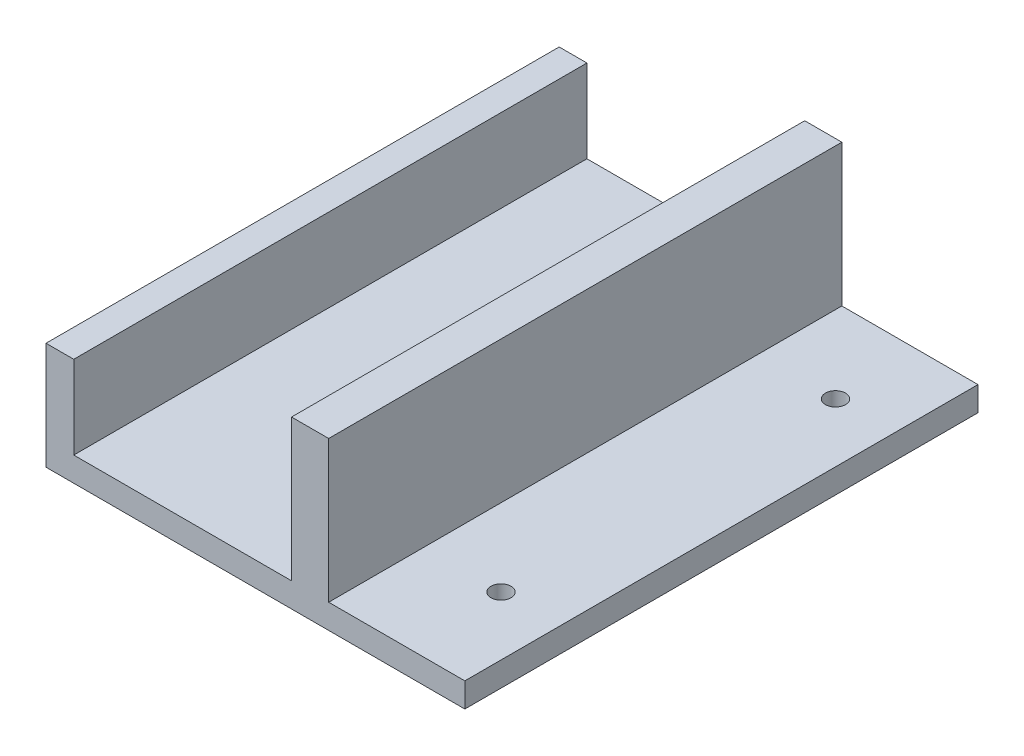
SolidWorks part; units mm, degrees
ref_plane "Front Plane" through (0, 0, 0) normal (0, 0, 1) x (1, 0, 0)
ref_plane "Top Plane" through (0, 0, 0) normal (0, 1, 0) x (1, 0, 0)
ref_plane "Right Plane" through (0, 0, 0) normal (1, 0, 0) x (0, 0, -1)
sketch "Sketch1" plane through (0, 0, 0) normal (0, 0, 1) x (1, 0, 0)
  line L0 (-62.6, 3.65) -> (-62.6, 28.45)
  line L1 (-62.6, 3.65) -> (62.6, 3.65)
  line L2 (-62.6, 3.65) -> (-62.6, -3.65)
  line L3 (-62.6, -3.65) -> (62.6, -3.65)
  line L4 (62.6, 3.65) -> (62.6, -3.65)
  line L5 (-62.6, 3.65) -> (62.6, -3.65) construction
  line L6 (-62.6, -3.65) -> (62.6, 3.65) construction
  line L7 (-62.6, 28.45) -> (-54.3, 28.45)
  line L8 (-54.3, 28.45) -> (-54.3, 3.65)
  line L9 (-54.3, 3.65) -> (-62.6, 3.65)
  line L10 (21.9, 3.65) -> (21.9, 46.05)
  line L11 (21.9, 46.05) -> (10.8, 46.05)
  line L12 (10.8, 46.05) -> (10.8, 3.65)
  line L13 (10.8, 3.65) -> (21.9, 3.65)
  point P0 (0, 0)
  dimension "D1" = 7.3
  dimension "D2" = 125.2
  dimension "D3" = 24.8
  dimension "D4" = 8.3
  dimension "D5" = 65.1
  dimension "D6" = 11.1
  dimension "D7" = 42.4
extrude "Boss-Extrude1" add sketch "Sketch1" along normal blind 153.4 contours L8 L7 L0 L1 | L4 L1 L2 L3 | L11 L12 L1 L10
sketch "Sketch2" plane through (0, 3.65, 0) normal (0, 1, 0) x (1, 0, 0)
  line L0 (45, -25) -> (45, 0) construction
  line L1 (21.9, 0) -> (62.6, 0) construction
  line L2 (45, -25) -> (62.6, -25) construction
  line L3 (62.6, -153.4) -> (62.6, 0) construction
  circle A0 centre (45, -25) radius 3
  dimension "D1" = 6
  dimension "D2" = 45
  dimension "D3" = 25
extrude "Cut-Extrude1" cut sketch "Sketch2" against normal blind 153.4
pattern_linear "LPattern1" count 2 spacing 100 along (0, 0, 1) of "Cut-Extrude1"
